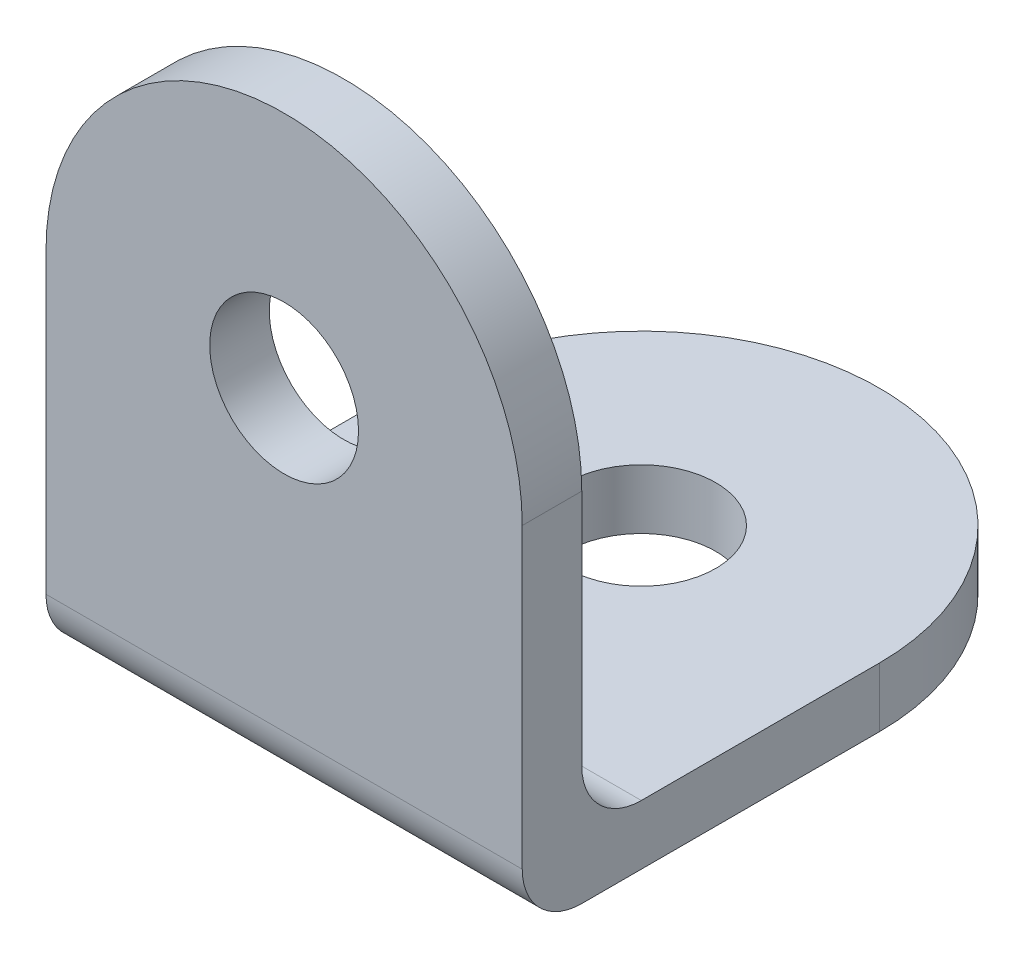
SolidWorks part; units mm, degrees
ref_plane "前视基准面" through (0, 0, 0) normal (0, 0, 1) x (1, 0, 0)
ref_plane "上视基准面" through (0, 0, 0) normal (0, 1, 0) x (1, 0, 0)
ref_plane "右视基准面" through (0, 0, 0) normal (1, 0, 0) x (0, 0, -1)
sketch "草图2" plane through (0, 0, 0) normal (0, 1, 0) x (1, 0, 0)
  line L1 (0, 0) -> (16, 0)
  line L2 (0, 0) -> (0, 12)
  line L4 (16, 0) -> (16, 12)
  arc A0 (16, 12) -> (0, 12) centre (8, 12) ccw
  circle A1 centre (8, 12) radius 2.5
  point P7 (8, 20)
  dimension "D1" = 5
  dimension "D2" = 8
  dimension "D3" = 20
extrude "凸台-拉伸1" add sketch "草图2" along normal blind 2
sketch "草图3" plane through (0, 0, 0) normal (0, 0, 1) x (1, 0, 0)
  line L0 (16, 2) -> (16, 0) construction
  line L1 (0, 0) -> (16, 0)
  line L2 (0, 0) -> (0, 12)
  line L4 (16, 0) -> (16, 12)
  arc A0 (16, 12) -> (0, 12) centre (8, 12) ccw
  circle A1 centre (8, 12) radius 2.5
  dimension "D1" = 5
  dimension "D2" = 12
extrude "凸台-拉伸2" add sketch "草图3" against normal blind 2
fillet "圆角1" radius 2 2 edges at (8, 0, 0) (8, 2, -2)
